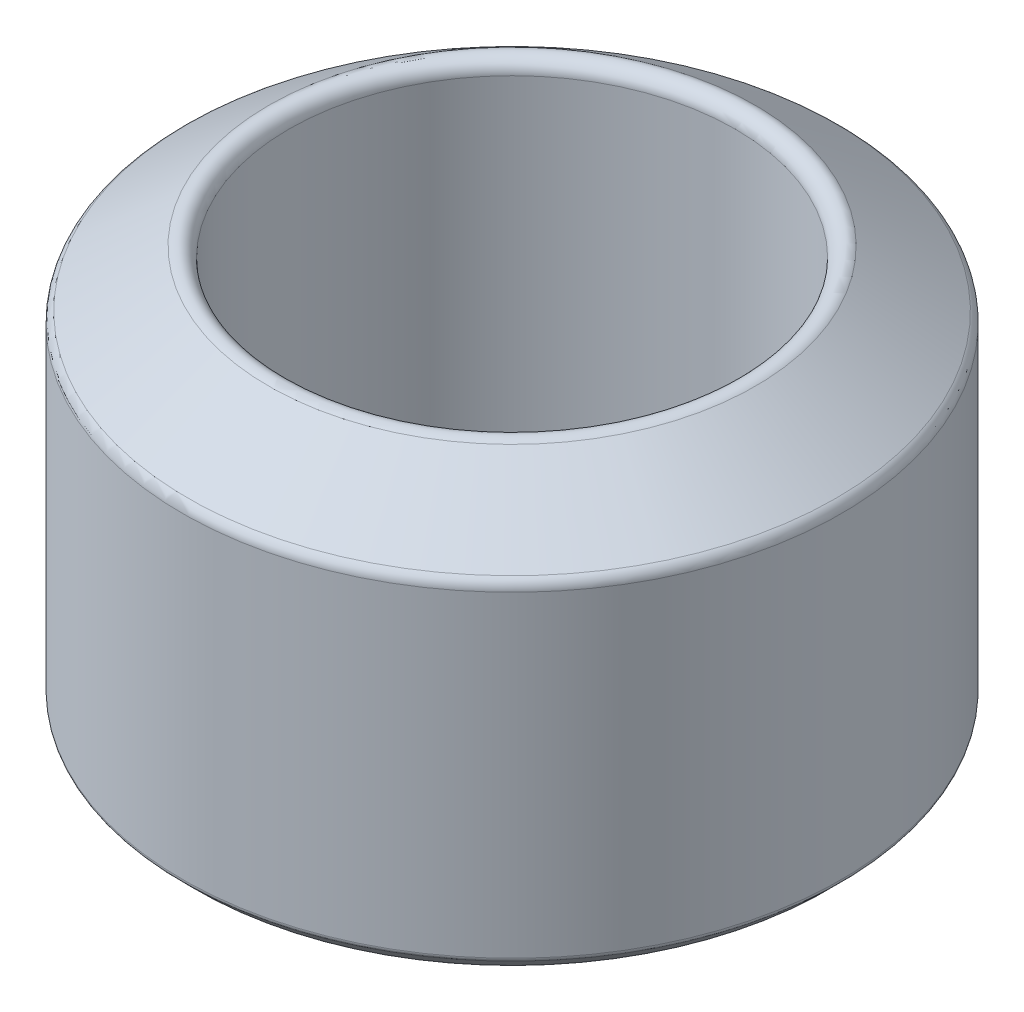
SolidWorks part; units mm, degrees
material "Rubber"
ref_plane "Front Plane" through (0, 0, 0) normal (0, 0, 1) x (1, 0, 0)
ref_plane "Top Plane" through (0, 0, 0) normal (0, 1, 0) x (1, 0, 0)
ref_plane "Right Plane" through (0, 0, 0) normal (1, 0, 0) x (0, 0, -1)
sketch "Main Revolve Sketch" plane through (0, 0, 0) normal (0, 0, 1) x (1, 0, 0)
  line L0 (0, 79.3047) -> (0, 39.8503) construction
  line L1 (-4.35, 0.6914) -> (-4.35, 7.6227)
  line L3 (-4.7434, 7.8275) -> (-6.3184, 6.7246)
  line L4 (-6.425, 6.5199) -> (-6.425, 0.3414)
  line L5 (-6.0836, 0) -> (-5.0414, 0)
  line L6 (-4.3793, 0.6207) -> (-4.9707, 0.0293)
  line L8 (-6.1543, 0.0293) -> (-6.3957, 0.2707)
  arc A1 (-4.35, 7.6227) -> (-4.7434, 7.8275) centre (-4.6, 7.6227) ccw
  arc A2 (-6.3184, 6.7246) -> (-6.425, 6.5199) centre (-6.175, 6.5199) ccw
  arc A5 (-6.3957, 0.2707) -> (-6.425, 0.3414) centre (-6.325, 0.3414) cw
  arc A6 (-6.1543, 0.0293) -> (-6.0836, 0) centre (-6.0836, 0.1) ccw
  arc A7 (-4.9707, 0.0293) -> (-5.0414, 0) centre (-5.0414, 0.1) cw
  arc A8 (-4.3793, 0.6207) -> (-4.35, 0.6914) centre (-4.45, 0.6914) ccw
  point P11 (-6.425, 6.65)
  point P14 (-6.425, 0)
  point P16 (-6.425, 0.3)
  point P17 (-4.35, 0)
  point P22 (-6.125, 0)
  point P25 (-5, 0)
  point P28 (-4.35, 0.65)
  dimension "D6" = 0.25
  dimension "D1" = 0.25
  dimension "D11" = 0.1
  dimension "D2" = 8.7
  dimension "D3" = 6.65
  dimension "D4" = 12.85
  dimension "D5" = 125
  dimension "D7" = 0.65
  dimension "D8" = 45
  dimension "D9" = 0.3
  dimension "D10" = 45
revolve "Main Revolve" add sketch "Main Revolve Sketch" angle 360 about L0
